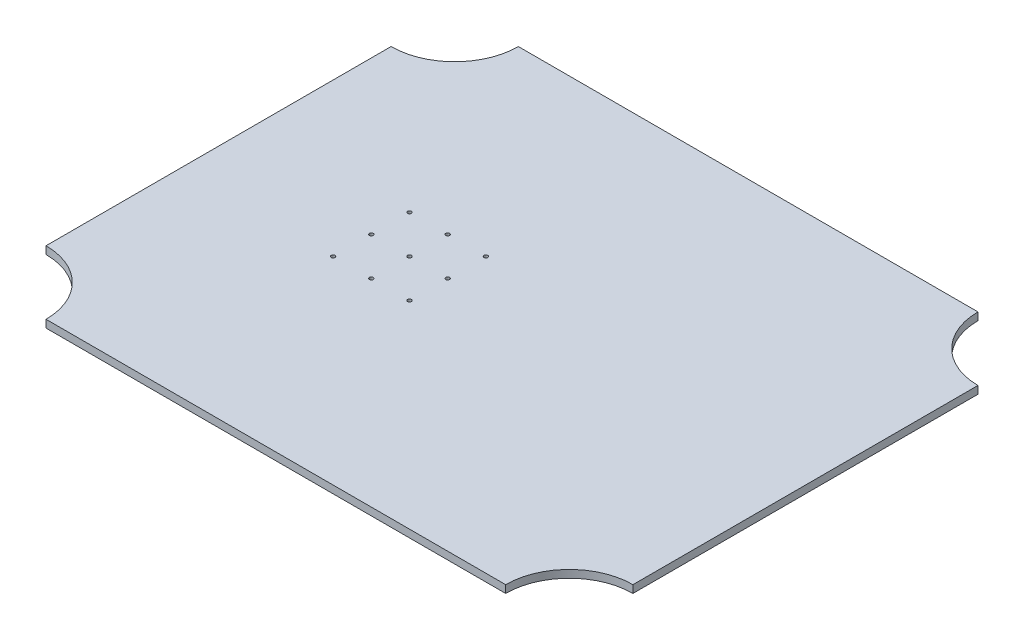
SolidWorks part; units mm, degrees
material "有机玻璃 (TM) GS 丙烯酸铸钣"
ref_plane "前视基准面" through (0, 0, 0) normal (0, 0, 1) x (1, 0, 0)
ref_plane "上视基准面" through (0, 0, 0) normal (0, 1, 0) x (1, 0, 0)
ref_plane "右视基准面" through (0, 0, 0) normal (1, 0, 0) x (0, 0, -1)
other "Configuration Table"
sketch "草图1" plane through (0, 0, 0) normal (0, 1, 0) x (1, 0, 0)
  line L0 (1200.8128, 0) -> (1661.8128, 0) construction
  line L1 (1250.8128, 185.5) -> (1611.8128, 185.5)
  line L2 (1200.8128, 135.5) -> (1200.8128, -135.5)
  line L3 (1250.8128, -185.5) -> (1611.8128, -185.5)
  line L4 (1661.8128, 135.5) -> (1661.8128, -135.5)
  line L7 (1350.8128, 307.4308) -> (1350.8128, -288.0385) construction
  line L8 (1320.8128, 185.5) -> (1320.8128, -185.5) construction
  line L9 (1661.8128, 199.7584) -> (1661.8128, -200.2416) construction
  arc A0 (1200.8128, 135.5) -> (1250.8128, 185.5) centre (1200.8128, 185.5) ccw
  arc A1 (1611.8128, 185.5) -> (1661.8128, 135.5) centre (1661.8128, 185.5) ccw
  arc A2 (1661.8128, -135.5) -> (1611.8128, -185.5) centre (1661.8128, -185.5) ccw
  arc A3 (1250.8128, -185.5) -> (1200.8128, -135.5) centre (1200.8128, -185.5) ccw
  circle A4 centre (1320.8128, 0) radius 1.5
  circle A5 centre (1320.8128, 30) radius 1.5
  circle A6 centre (1350.8128, 30) radius 1.5
  circle A8 centre (1350.8128, 0) radius 1.5
  circle A11 centre (1350.8128, -30) radius 1.5
  circle A12 centre (1320.8128, -30) radius 1.5
  circle A13 centre (1380.8128, -30) radius 1.5
  circle A14 centre (1380.8128, 0) radius 1.5
  circle A15 centre (1380.8128, 30) radius 1.5
  dimension "D3" = 100
  dimension "D6" = 3
  dimension "D1" = 371
  dimension "D2" = 461
  dimension "D4" = 30
  dimension "D5" = 150
  dimension "D7" = 60
  dimension "D8" = 60
extrude "凸台-拉伸1" add sketch "草图1" along normal blind 6
